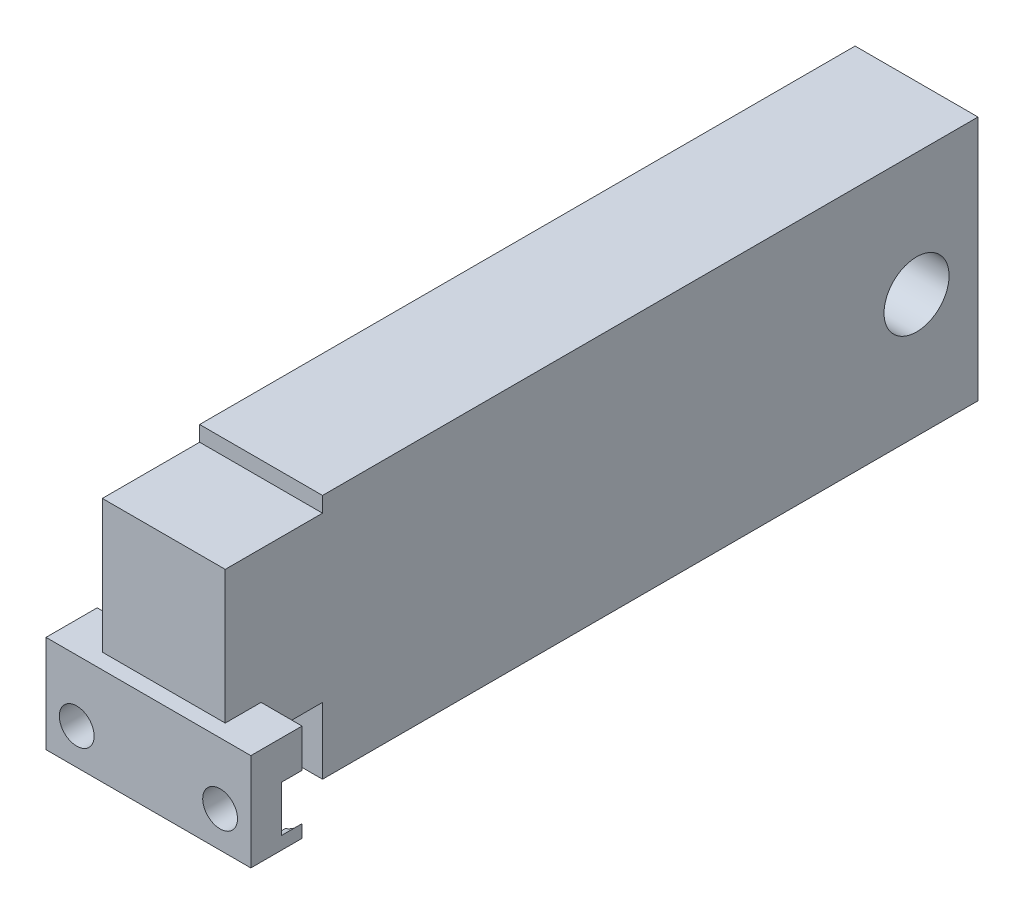
SolidWorks part; units mm, degrees
material "7075-T6 (SN)"
ref_plane "Front Plane" through (0, 0, 0) normal (0, 0, 1) x (1, 0, 0)
ref_plane "Top Plane" through (0, 0, 0) normal (0, 1, 0) x (1, 0, 0)
ref_plane "Right Plane" through (0, 0, 0) normal (1, 0, 0) x (0, 0, -1)
sketch "Sketch1" plane through (0, 0, 0) normal (0, 0, 1) x (1, 0, 0)
  line L1 (-30, 24.5) -> (-10, 24.5)
  line L2 (-30, 24.5) -> (-30, 34)
  line L3 (-30, 34) -> (-10, 34)
  line L4 (-10, 24.5) -> (-10, 34)
  circle A0 centre (-27, 28) radius 1.7
  circle A1 centre (-13, 28) radius 1.7
extrude "Five_mm_Attachment_Foot" add sketch "Sketch1" along normal blind 5 from offset 5
sketch "Sketch2" plane through (0, 0, 0) normal (0, 0, 1) x (1, 0, 0)
  line L1 (-26, 24.5) -> (-14, 24.5)
  line L2 (-26, 24.5) -> (-26, 48.5)
  line L3 (-26, 48.5) -> (-14, 48.5)
  line L4 (-14, 24.5) -> (-14, 48.5)
extrude "Deep_Actuator_Web" add sketch "Sketch2" along normal blind 67.5 from offset 69
sketch "Sketch3" plane through (0, 0, 0) normal (1, 0, 0) x (0, 0, -1)
  circle A0 centre (69, 36.5) radius 3.175
extrude "Quarter20_Axial_Thread_Major_Envelope" cut sketch "Sketch3" against normal through all and the other way through all
sketch "Sketch4" plane through (0, 0, 0) normal (0, 0, 1) x (1, 0, 0)
  line L1 (-26, 24.5) -> (-14, 24.5)
  line L2 (-26, 24.5) -> (-26, 48.5)
  line L3 (-26, 48.5) -> (-14, 48.5)
  line L4 (-14, 24.5) -> (-14, 48.5)
extrude "Bench_X_Bore_Lower_Ligament" add sketch "Sketch4" along normal blind 6.01 from offset 75
sketch "Sketch5" plane through (0, 0, 0) normal (1, 0, 0) x (0, 0, -1)
  circle A0 centre (69, 36.5) radius 3.175
extrude "Bench_Complete_Quarter20_Major_Envelope" cut sketch "Sketch5" against normal through all and the other way through all
sketch "Sketch6" plane through (0, 0, 0) normal (1, 0, 0) x (0, 0, -1)
  line L0 (11, 24) -> (11, 31)
  line L1 (11, 31) -> (5, 31)
  line L2 (5, 31) -> (5, 24)
  line L3 (5, 24) -> (11, 24)
  line L4 (11, 47) -> (11, 49)
  line L5 (11, 49) -> (1, 49)
  line L6 (1, 49) -> (1, 47)
  line L7 (1, 47) -> (11, 47)
extrude "Fixed_Base_Window_Relief" cut sketch "Sketch6" against normal through all and the other way through all
sketch "Sketch7" plane through (0, 0, 0) normal (0, 0, 1) x (1, 0, 0)
  circle A0 centre (-27, 28) radius 1.7
  circle A1 centre (-13, 28) radius 1.7
extrude "XDrop_M3_Through_Recut" cut sketch "Sketch7" against normal blind 5.5
sketch "Sketch8" plane through (0, 0, -5) normal (0, 0, -1) x (-1, 0, 0)
  circle A0 centre (27, 28) radius 3.75
  circle A1 centre (13, 28) radius 3.75
extrude "XDrop_M3_Bottom_Counterbore_H2" cut sketch "Sketch8" against normal blind 2
